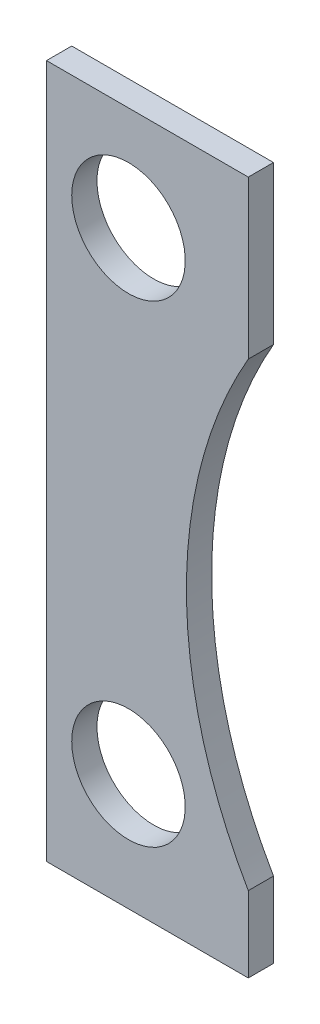
SolidWorks part; units mm, degrees
ref_plane "Ön Düzlem" through (0, 0, 0) normal (0, 0, 1) x (1, 0, 0)
ref_plane "Üst Düzlem" through (0, 0, 0) normal (0, 1, 0) x (1, 0, 0)
ref_plane "Sağ Düzlem" through (0, 0, 0) normal (1, 0, 0) x (0, 0, -1)
sketch "Çizim1" plane through (0, 0, 0) normal (0, 0, 1) x (1, 0, 0)
  line L0 (0, 110) -> (32, 110)
  line L1 (0, 110) -> (0, 0)
  line L2 (0, 0) -> (32, 0)
  line L3 (32, 110) -> (32, 85)
  line L4 (32, 12) -> (32, 0)
  arc A0 (32, 85) -> (32, 12) centre (95, 48.5) ccw
  dimension "D1" = 110
  dimension "D2" = 32
  dimension "D3" = 25
  dimension "D4" = 12
  dimension "D5" = 95
extrude "Yükseklik-Ekstrüzyon1" add sketch "Çizim1" along normal mid plane 4
sketch "Çizim2" plane through (0, 0, -2) normal (0, 0, -1) x (-1, 0, 0)
  line L0 (0, 110) -> (0, 0) construction
  line L1 (-32, 110) -> (0, 110) construction
  circle A0 centre (-13, 93.5) radius 9
  circle A1 centre (-13, 18.5) radius 9
  dimension "D3" = 18
  dimension "D1" = 75
  dimension "D2" = 13
  dimension "D4" = 16.5
extrude "Kes-Ekstrüzyon1" cut sketch "Çizim2" against normal through all
